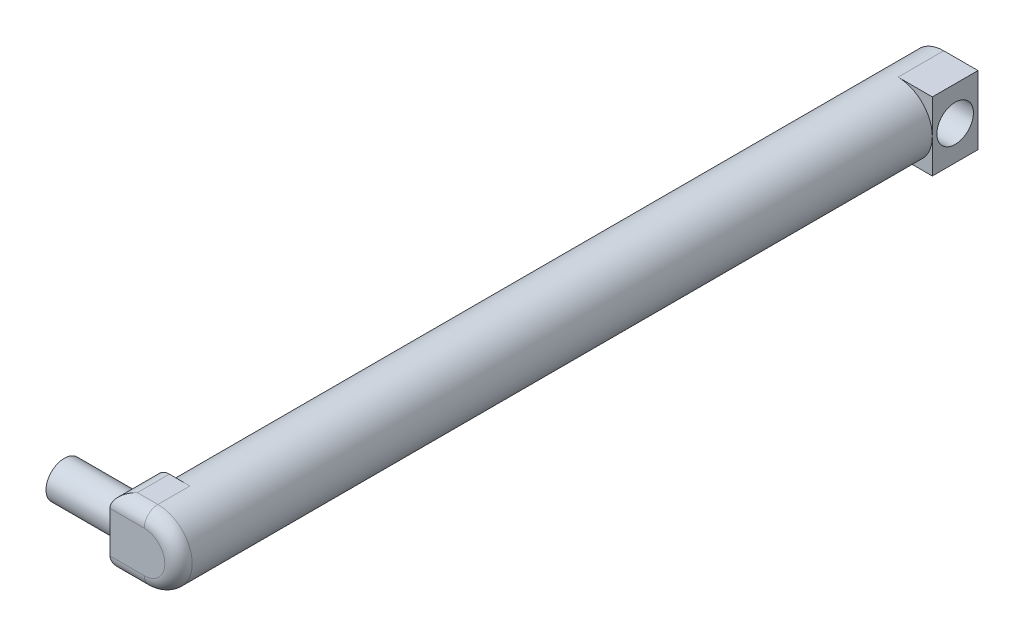
SolidWorks part; units mm, degrees
ref_plane "前视基准面" through (0, 0, 0) normal (0, 0, 1) x (1, 0, 0)
ref_plane "上视基准面" through (0, 0, 0) normal (0, 1, 0) x (1, 0, 0)
ref_plane "右视基准面" through (0, 0, 0) normal (1, 0, 0) x (0, 0, -1)
other "Configuration Table"
sketch "草图1" plane through (0, 0, 0) normal (0, 0, 1) x (1, 0, 0)
  circle A0 centre (0, 0) radius 7.5
  dimension "D1" = 15
extrude "凸台-拉伸1" add sketch "草图1" along normal mid plane 175
sketch "草图2" plane through (0, 0, 0) normal (1, 0, 0) x (0, 0, -1)
  line L0 (87.5, 7.5) -> (-87.5, 7.5) construction
  line L1 (-87.5, -7.5) -> (-77.5, -7.5)
  line L2 (-87.5, -7.5) -> (-87.5, 7.5)
  line L3 (-87.5, 7.5) -> (-77.5, 7.5)
  line L4 (-77.5, -7.5) -> (-77.5, 7.5)
  dimension "D1" = 10
extrude "凸台-拉伸2" add sketch "草图2" against normal blind 7.5
sketch "草图3" plane through (-7.5, 0, 0) normal (-1, 0, 0) x (0, 0, 1)
  line L0 (87.5, 7.5) -> (77.5, -7.5) construction
  line L1 (87.5, -7.5) -> (77.5, 7.5) construction
  circle A0 centre (82.5, 0) radius 4
  dimension "D1" = 8
extrude "凸台-拉伸3" add sketch "草图3" along normal blind 15
sketch "草图4" plane through (0, 0, 0) normal (1, 0, 0) x (0, 0, -1)
  line L0 (87.5, 7.5) -> (-77.5, 7.5) construction
  line L1 (87.5, -7.5) -> (77.5, -7.5)
  line L2 (87.5, -7.5) -> (87.5, 7.5)
  line L3 (87.5, 7.5) -> (77.5, 7.5)
  line L4 (77.5, -7.5) -> (77.5, 7.5)
  dimension "D1" = 10
extrude "凸台-拉伸4" add sketch "草图4" along normal blind 7.5
sketch "草图5" plane through (7.5, 0, 0) normal (1, 0, 0) x (0, 0, -1)
  line L0 (87.5, 7.5) -> (77.5, 7.5) construction
  circle A0 centre (82.5, 0) radius 4
  point P6 (82.5, 7.5)
  dimension "D1" = 8
extrude "切除-拉伸1" cut sketch "草图5" against normal blind 15
fillet "圆角1" radius 3 5 edges at (-3.75, -7.5, 87.5) (7.5, 0, 87.5) (-7.5, 7.5, 82.5) (-3.75, 7.5, 87.5) (-7.5, -7.5, 82.5)
